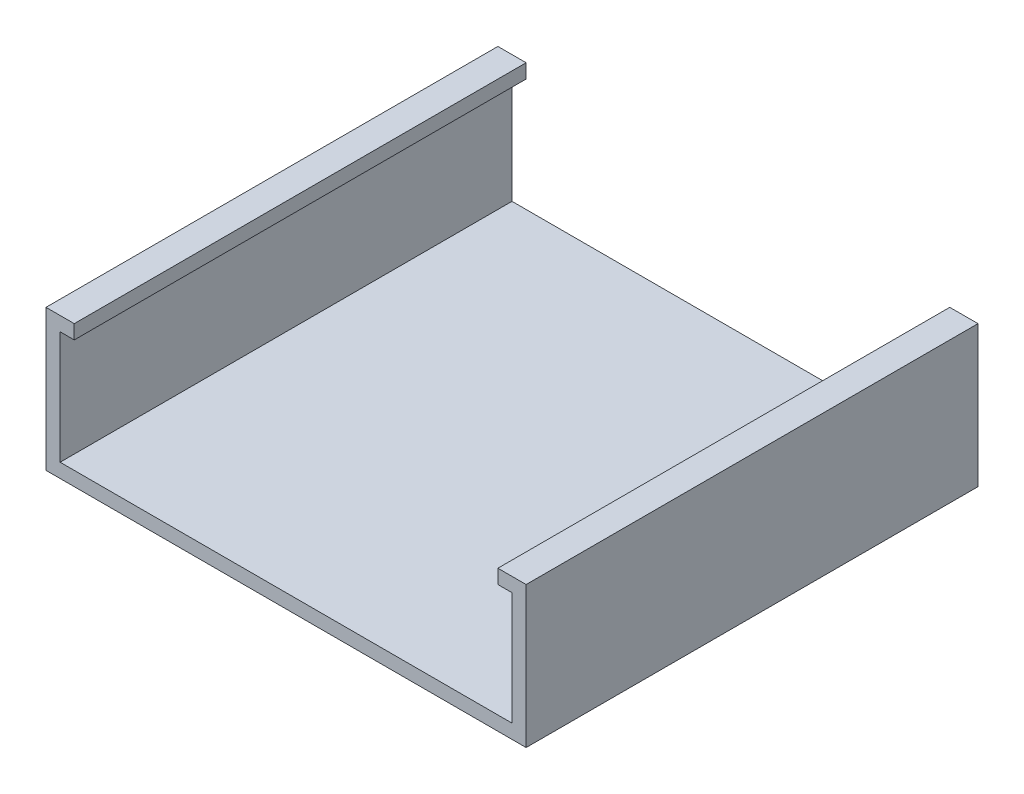
SolidWorks part; units mm, degrees
ref_plane "Front Plane" through (0, 0, 0) normal (0, 0, 1) x (1, 0, 0)
ref_plane "Top Plane" through (0, 0, 0) normal (0, 1, 0) x (1, 0, 0)
ref_plane "Right Plane" through (0, 0, 0) normal (1, 0, 0) x (0, 0, -1)
sketch "Sketch1" plane through (0, 0, 0) normal (0, 1, 0) x (1, 0, 0)
  line L1 (-85, 80) -> (85, 80)
  line L2 (-85, 80) -> (-85, -80)
  line L3 (-85, -80) -> (85, -80)
  line L4 (85, 80) -> (85, -80)
  line L5 (-85, 80) -> (85, -80) construction
  line L6 (-85, -80) -> (85, 80) construction
  point P0 (0, 0)
  dimension "D1" = 170
  dimension "D2" = 160
extrude "Boss-Extrude2" add sketch "Sketch1" along normal blind 50
sketch "Sketch3" plane through (0, 0, 80) normal (0, 0, 1) x (1, 0, 0)
  line L0 (-85, 50) -> (85, 50) construction
  line L1 (-80, 45) -> (80, 45)
  line L2 (-80, 45) -> (-80, 5)
  line L3 (-80, 5) -> (80, 5)
  line L4 (80, 45) -> (80, 5)
  line L5 (85, 50) -> (85, 0) construction
  line L6 (-85, 0) -> (85, 0) construction
  line L7 (-85, 50) -> (-85, 0) construction
  dimension "D1" = 5
  dimension "D2" = 5
  dimension "D3" = 5
  dimension "D4" = 5
extrude "Cut-Extrude2" cut sketch "Sketch3" against normal up to next
sketch "Sketch4" plane through (0, 50, 0) normal (0, 1, 0) x (1, 0, 0)
  line L0 (85, 80) -> (-85, 80) construction
  line L1 (-75, 80) -> (75, 80)
  line L2 (-75, 80) -> (-75, -80)
  line L3 (-75, -80) -> (75, -80)
  line L4 (75, 80) -> (75, -80)
  line L5 (-85, -80) -> (85, -80) construction
  line L6 (-85, 80) -> (-85, -80) construction
  line L7 (85, -80) -> (85, 80) construction
  dimension "D1" = 10
  dimension "D2" = 10
extrude "Cut-Extrude3" cut sketch "Sketch4" against normal up to next
